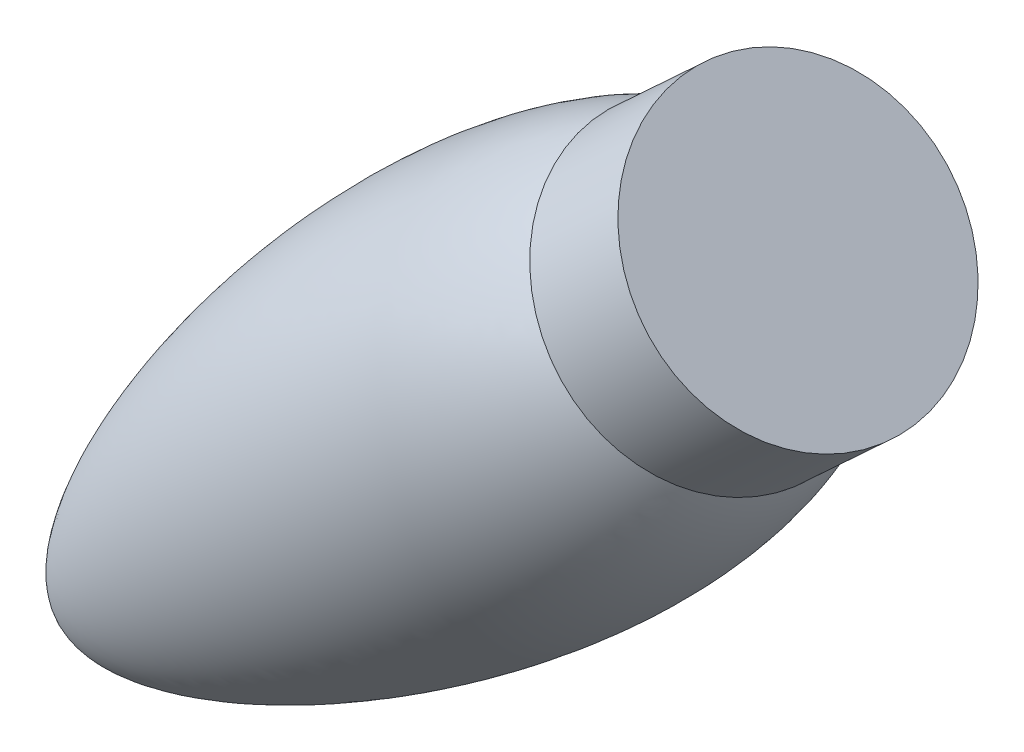
SolidWorks part; units mm, degrees
ref_plane "前基準面" through (0, 0, 0) normal (0, 0, 1) x (1, 0, 0)
ref_plane "上基準面" through (0, 0, 0) normal (0, 1, 0) x (1, 0, 0)
ref_plane "右基準面" through (0, 0, 0) normal (1, 0, 0) x (0, 0, -1)
sketch "草圖1" plane through (0, 0, 0) normal (0, 0, 1) x (1, 0, 0)
  line L0 (-23.337, 14.5322) -> (-26.5665, 3.2409)
  line L1 (-26.5665, 3.2409) -> (-45.3418, -14.1409)
  spline S0 degree 3 poles (-23.337, 14.5322) (-35.1045, 9.8178) (-48.6238, -11.0632) (-45.3418, -14.1409) knots 0 0 0 0 0.69219 0.69219 0.69219 0.69219
revolve "旋轉1" add sketch "草圖1" angle 360 about L1
ref_plane "平面1" through (-5.322, -4.927, 0) normal (-0.7338, -0.6794, 0) x (0, 0, 1)
sketch "草圖2" plane through (-5.322, -4.927, 0) normal (-0.7338, -0.6794, 0) x (0, 0, 1)
  circle A0 centre (0, 20.5386) radius 6.2041
extrude "填料-伸長1" add sketch "草圖2" against normal blind 5 separate body
